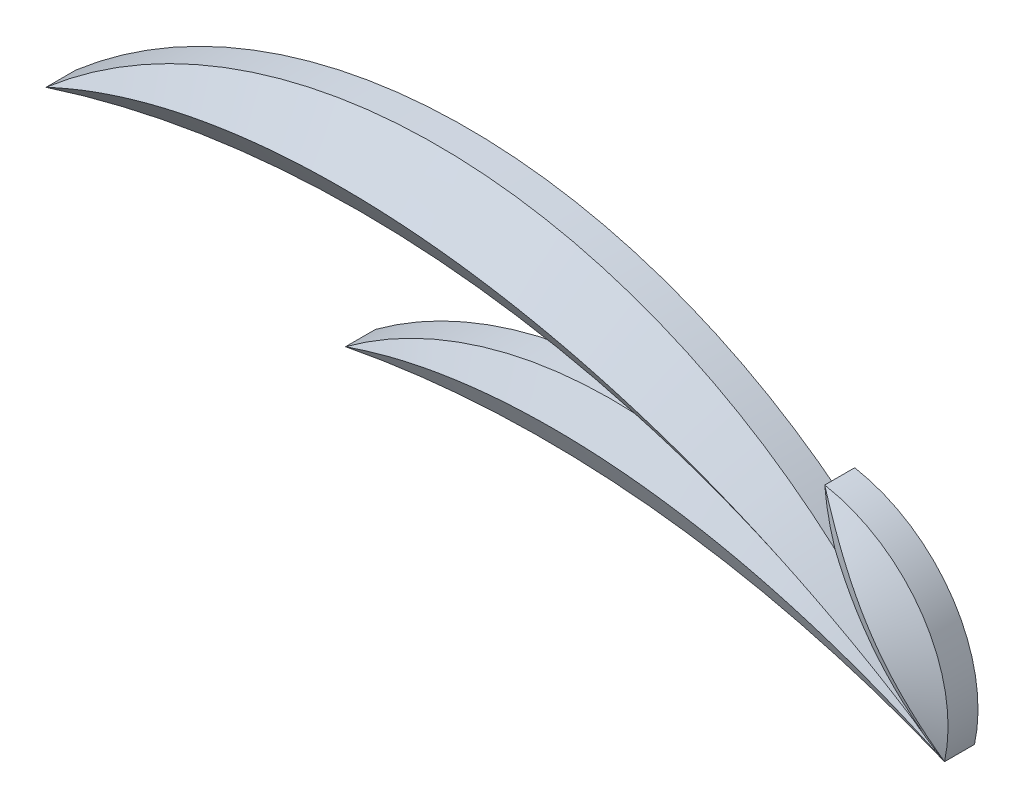
SolidWorks part; units mm, degrees
ref_plane "Plano frontal" through (0, 0, 0) normal (0, 0, 1) x (1, 0, 0)
ref_plane "Plano superior" through (0, 0, 0) normal (0, 1, 0) x (1, 0, 0)
ref_plane "Plano direito" through (0, 0, 0) normal (1, 0, 0) x (0, 0, -1)
sketch "Esboço1" plane through (0, 0, 0) normal (0, 0, 1) x (1, 0, 0)
  spline S0 degree 2 poles (0, 0) (-18.1517, 12.2016) (-40, 4) knots 0 0 0 1 1 1 construction
  spline S1 degree 3 poles (0, 0) (-13.7782, 18.1009) (-41.168, 18.842) (-60, 9) knots 0 0 0 0 1 1 1 1 construction
  spline S2 degree 2 poles (0, 0) (-1.9597, 7.2357) (-8, 12) knots 0 0 0 1 1 1 construction
  dimension "D1" = 2
  dimension "D2" = 8
  dimension "D3" = 13
  dimension "D4" = 16
  dimension "D5" = 40
  dimension "D6" = 50
  dimension "D7" = 60
  dimension "D8" = 4
  dimension "D9" = 5
  dimension "D10" = 6
  dimension "D11" = 9
  dimension "D12" = 12
  dimension "D13" = 12
  dimension "D14" = 13
sketch "Esboço2" plane through (0, 0, 0) normal (0, 0, 1) x (1, 0, 0)
  arc A6 (0, 0) -> (-8, 12) centre (-9.7646, 2.1569) ccw
  arc A7 (0, 0) -> (-8, 12) centre (6.9439, 13.2959) cw
  arc A8 (-60, 9) -> (0, 0) centre (-33.8675, -21.2836) cw
  arc A9 (-60, 9) -> (0, 0) centre (-39.0278, -55.6851) cw
  arc A10 (-40, 4) -> (0, 0) centre (-22.2161, -20.1605) cw
  arc A11 (-40, 4) -> (0, 0) centre (-26.6719, -64.7195) cw
  dimension "D1" = 10
  dimension "D2" = 15
  dimension "D3" = 40
  dimension "D4" = 68
  dimension "D5" = 30
  dimension "D6" = 70
sketch "Esboço3" plane through (0, 0, 0) normal (0, 0, 1) x (1, 0, 0)
  arc A0 (-8, 12) -> (0, 0) centre (-9.7646, 2.1569) cw
  arc A1 (-8, 12) -> (0, 0) centre (6.9439, 13.2959) ccw
  arc A4 (0, 0) -> (-8, 12) centre (-9.7646, 2.1569) ccw construction
  arc A5 (-8, 12) -> (0, 0) centre (6.9439, 13.2959) ccw construction
extrude "Ressalto-extrusão1" add sketch "Esboço3" along normal blind 15 draft 60
sketch "Esboço4" plane through (0, 0, 0) normal (0, 0, 1) x (1, 0, 0)
  arc A0 (-60, 9) -> (0, 0) centre (-33.8675, -21.2836) cw
  arc A1 (-60, 9) -> (0, 0) centre (-39.0278, -55.6851) cw
  arc A4 (0, 0) -> (-60, 9) centre (-33.8675, -21.2836) ccw construction
  arc A5 (0, 0) -> (-60, 9) centre (-39.0278, -55.6851) ccw construction
extrude "Ressalto-extrusão2" add sketch "Esboço4" along normal blind 5 draft 53
sketch "Esboço5" plane through (0, 0, 0) normal (0, 0, 1) x (1, 0, 0)
  arc A0 (-40, 4) -> (0, 0) centre (-22.2161, -20.1605) cw
  arc A1 (-40, 4) -> (0, 0) centre (-26.6719, -64.7195) cw
  arc A4 (0, 0) -> (-40, 4) centre (-22.2161, -20.1605) ccw construction
  arc A5 (0, 0) -> (-40, 4) centre (-26.6719, -64.7195) ccw construction
extrude "Ressalto-extrusão3" add sketch "Esboço5" along normal blind 5 draft 60
sketch "Esboço6" plane through (0, 0, 0) normal (0, 0, 1) x (1, 0, 0)
  arc A0 (0, 0) -> (-8, 12) centre (-9.7646, 2.1569) ccw
  arc A1 (-7.3118, 8.6295) -> (-8, 12) centre (6.9439, 13.2959) cw
  arc A2 (-60, 9) -> (-7.3118, 8.6295) centre (-33.8675, -21.2836) cw
  arc A3 (-60, 9) -> (-20.7119, 9.8017) centre (-39.0278, -55.6851) cw
  arc A4 (-20.7119, 9.8017) -> (-40, 4) centre (-22.2161, -20.1605) ccw
  arc A5 (-40, 4) -> (0, 0) centre (-26.6719, -64.7195) cw
  arc A6 (0, 0) -> (-8, 12) centre (-9.7646, 2.1569) ccw construction
  arc A13 (-8, 12) -> (-7.3118, 8.6295) centre (6.9439, 13.2959) ccw construction
  arc A14 (-7.3118, 8.6295) -> (-60, 9) centre (-33.8675, -21.2836) ccw construction
  arc A15 (-20.7119, 9.8017) -> (-60, 9) centre (-39.0278, -55.6851) ccw construction
  arc A16 (-20.7119, 9.8017) -> (-40, 4) centre (-22.2161, -20.1605) ccw construction
  arc A17 (0, 0) -> (-40, 4) centre (-26.6719, -64.7195) ccw construction
extrude "Ressalto-extrusão4" add sketch "Esboço6" against normal blind 2
